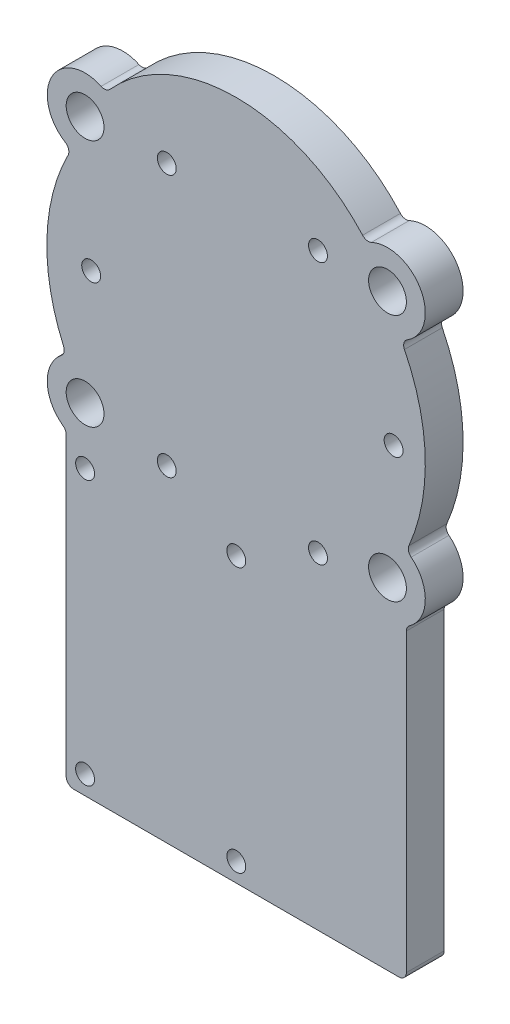
SolidWorks part; units mm, degrees
ref_plane "Front Plane" through (0, 0, 0) normal (0, 0, 1) x (1, 0, 0)
ref_plane "Top Plane" through (0, 0, 0) normal (0, 1, 0) x (1, 0, 0)
ref_plane "Right Plane" through (0, 0, 0) normal (1, 0, 0) x (0, 0, -1)
sketch "Sketch1" plane through (0, 0, 0) normal (0, 0, 1) x (1, 0, 0)
  line L0 (0, 0) -> (0, 4.5) construction
  line L1 (0, 0) -> (0, -9) construction
  line L2 (0, 4.5) -> (0, 9) construction
  line L4 (4.5, -9) -> (0, -9)
  line L5 (0, -9) -> (-4.5, -9)
  line L6 (-4.5, -9) -> (-4.5, -0.866)
  line L7 (-4.5, 0) -> (-4, 0) construction
  line L9 (4.5, -0.866) -> (4.5, -9)
  arc A0 (-4.5, 0.866) -> (-4.3565, 5.6273) centre (0.161, 3.1083) cw
  circle A1 centre (-4, 0) radius 0.5
  arc A2 (-4.5, 0.866) -> (-4.5, -0.866) centre (-4, 0) ccw
  arc A3 (-3.4459, 7.394) -> (-4.3565, 5.6273) centre (-4, 6.5616) ccw
  circle A4 centre (-4, 6.5616) radius 0.5
  arc A5 (4.3565, 5.6273) -> (4.5, 0.866) centre (-0.2641, 3.1052) cw
  circle A6 centre (4, 6.5616) radius 0.5
  arc A7 (3.4459, 7.394) -> (4.3565, 5.6273) centre (4, 6.5616) cw
  circle A8 centre (4, 0) radius 0.5
  arc A9 (4.5, 0.866) -> (4.5, -0.866) centre (4, 0) cw
  arc A10 (3.4459, 7.394) -> (-3.4459, 7.394) centre (0, 4.5) ccw
  dimension "D5" = 2
  dimension "D6" = 2
  dimension "D7" = 1
  dimension "D1" = 4.5
  dimension "D2" = 4.5
  dimension "D4" = 0.5
extrude "Boss-Extrude2" add sketch "Sketch1" along normal blind 1
fillet "Fillet2" radius 0.2 10 edges at (-4.5, -0.866, 0.5) (-4.5, 0.866, 0.5) (-4.3565, 5.6273, 0.5) (-3.4459, 7.394, 0.5) (3.4459, 7.394, 0.5) (4.3565, 5.6273, 0.5) (4.5, 0.866, 0.5) (4.5, -0.866, 0.5) (4.5, -9, 0.5) (-4.5, -9, 0.5)
sketch "Sketch3" plane through (0, 0, 0) normal (0, 0, -1) x (-1, 0, 0)
  circle A1 centre (3.839, 3.1083) radius 0.25
  circle A2 centre (1.839, -0.3558) radius 0.25
  circle A3 centre (-2.161, -0.3558) radius 0.25
  circle A4 centre (-4.161, 3.1083) radius 0.25
  circle A5 centre (-2.161, 6.5725) radius 0.25
  circle A6 centre (1.839, 6.5725) radius 0.25
  point P18 (-0.161, 3.1083)
  dimension "D2" = 0.5
  dimension "D3" = 6
extrude "Cut-Extrude1" cut sketch "Sketch3" against normal blind 1
sketch "Sketch4" plane through (0, 0, 0) normal (0, 0, -1) x (-1, 0, 0)
  line L0 (4, -8) -> (4, -1.5) construction
  line L1 (4, -8) -> (4, -8.5) construction
  circle A0 centre (4, -1.5) radius 0.25
  circle A1 centre (4, -8.5) radius 0.25
  circle A2 centre (0, -1.5) radius 0.25
  circle A3 centre (0, -8.5) radius 0.25
  dimension "D3" = 0.5
  dimension "D4" = 0.5
  dimension "D5" = 0.5
  dimension "D6" = 0.5
  dimension "D1" = 0.5
  dimension "D2" = 6.5
extrude "Cut-Extrude2" cut sketch "Sketch4" against normal blind 1
